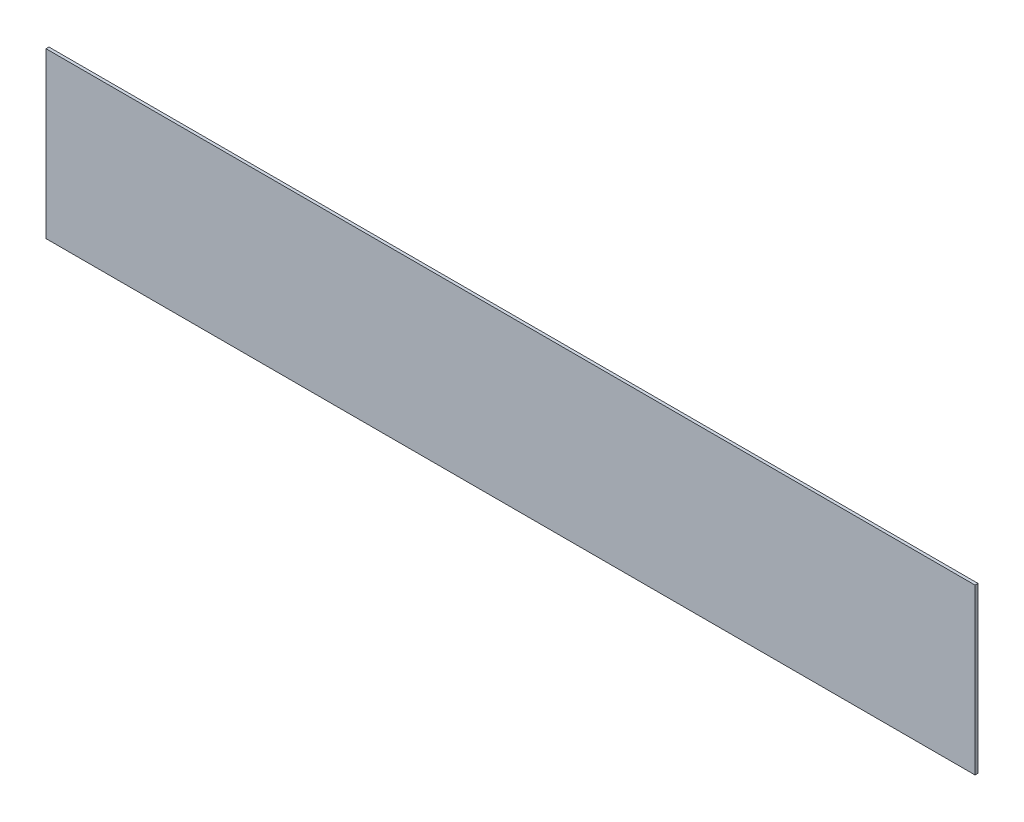
SolidWorks part; units mm, degrees
ref_plane "Front Plane" through (0, 0, 0) normal (0, 0, 1) x (1, 0, 0)
ref_plane "Top Plane" through (0, 0, 0) normal (0, 1, 0) x (1, 0, 0)
ref_plane "Right Plane" through (0, 0, 0) normal (1, 0, 0) x (0, 0, -1)
sketch "Sketch1" plane through (0, 0, 0) normal (0, 0, 1) x (1, 0, 0)
  line L0 (0, -88.519) -> (25.4, -88.519) construction
  line L1 (0, 0) -> (1000, 0)
  line L2 (0, 0) -> (0, -177.038)
  line L3 (0, -177.038) -> (1000, -177.038)
  line L4 (1000, 0) -> (1000, -177.038)
  dimension "D1" = 1000
  dimension "D2" = 177.038
extrude "Boss-Extrude1" add sketch "Sketch1" along normal blind 3.175
sketch "Sketch2" plane through (0, -177.038, 0) normal (0, -1, 0) x (1, 0, 0)
  line L0 (1000, 1.5875) -> (0, 1.5875) construction
  line L1 (1000, 3.175) -> (1000, 0) construction
  line L2 (0, 3.175) -> (0, 0) construction
sketch "Sketch4" plane through (0, 0, 0) normal (0, 1, 0) x (1, 0, 0)
  point P3 (0, -1.5875)
sketch "Sketch5" plane through (1000, 0, 0) normal (1, 0, 0) x (0, 0, -1)
  line L0 (-1.5875, 0) -> (-1.5875, -177.038) construction
  line L1 (-3.175, 0) -> (0, 0) construction
  line L2 (-3.175, -177.038) -> (0, -177.038) construction
sketch "Sketch6" plane through (0, 0, 0) normal (-1, 0, 0) x (0, 0, 1)
  line L0 (1.5875, 0) -> (1.5875, -177.038) construction
  line L1 (3.175, -177.038) -> (0, -177.038) construction
